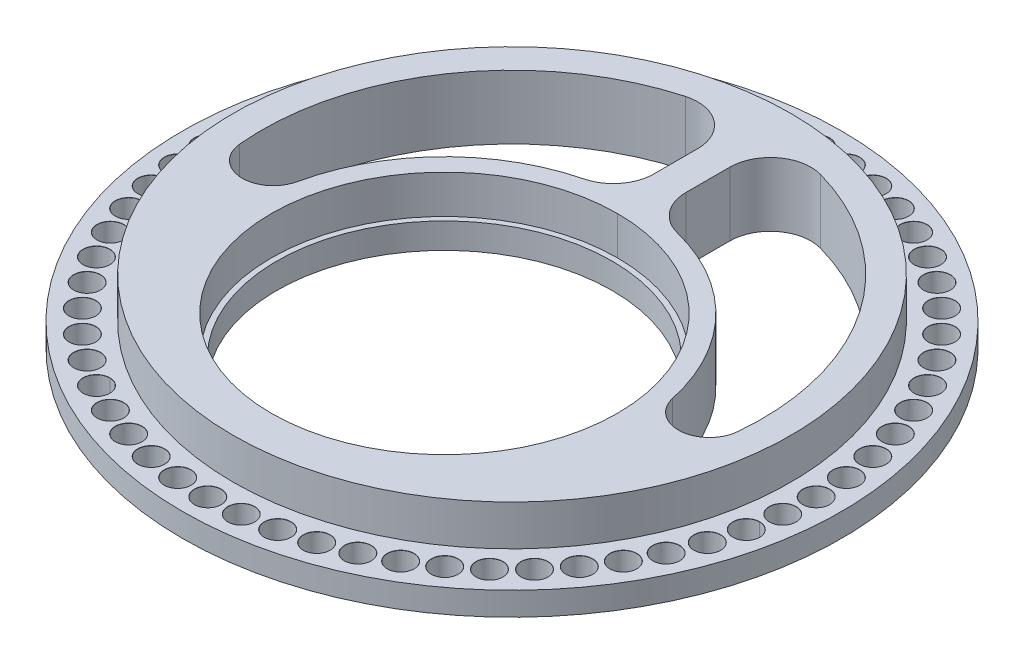
SolidWorks part; units mm, degrees
material "6061-T6 (SS)"
ref_plane "X-Y Datum" through (0, 0, 0) normal (0, 0, 1) x (1, 0, 0)
ref_plane "X-Z Datum" through (0, 0, 0) normal (0, 1, 0) x (1, 0, 0)
ref_plane "Y-Z Datum" through (0, 0, 0) normal (1, 0, 0) x (0, 0, -1)
sketch "Sketch1" plane through (0, 0, 0) normal (0, 1, 0) x (1, 0, 0)
  line L0 (0, 0) -> (0, -12.7) construction
  line L1 (0, -43.0151) -> (0, 43.0151) construction
  line L2 (0, 52.3875) -> (0, 61.9125) construction
  circle A0 centre (0, -12.7) radius 30.988
  circle A1 centre (0, 0) radius 52.3875 construction
  circle A2 centre (0, 0) radius 61.9125
  circle A3 centre (0, 0) radius 57.15 construction
  point P12 (0, 57.15)
  dimension "D2" = 61.976
  dimension "D3" = 104.775
  dimension "D4" = 123.825
  dimension "D5" = 114.3
  dimension "D1" = 12.7
extrude "Slotted-Body Extrude" add sketch "Sketch1" along normal blind 4.191 and the other way blind 0.2032
sketch "Sketch5" plane through (0, 4.191, 0) normal (0, 1, 0) x (1, 0, 0)
  circle A0 centre (0, 0) radius 52.3875 construction
  circle A1 centre (0, 0) radius 52.3875
extrude "Boss-Extrude3" add sketch "Sketch5" along normal blind 7.62
sketch "Sketch6" plane through (0, -0.2032, 0) normal (0, -1, 0) x (1, 0, 0)
  line L0 (0, -79.2756) -> (0, 0) construction
  line L2 (3.014, -37.9067) -> (3.014, -29.6741)
  line L4 (-3.014, -37.9067) -> (-3.014, -29.6741)
  circle A0 centre (0, 12.7) radius 30.988 construction
  circle A1 centre (0, 12.7) radius 30.988 construction
  circle A2 centre (0, 12.7) radius 32.512
  arc A9 (-35.2562, 5.0907) -> (-8.7792, -22.2832) centre (0, 12.7) ccw
  arc A10 (-46.783, 4.406) -> (-12.6921, -45.2435) centre (0, 0) ccw
  arc A11 (-46.783, 4.406) -> (-35.2562, 5.0907) centre (-40.9667, 3.8583) cw
  arc A19 (-3.014, -29.6741) -> (-8.7792, -22.2832) centre (-10.634, -29.6741) ccw
  arc A20 (-3.014, -37.9067) -> (-12.6921, -45.2435) centre (-10.634, -37.9067) cw
  circle A21 centre (0, 0) radius 61.9125 construction
  arc A27 (46.783, 4.406) -> (35.2562, 5.0907) centre (40.9667, 3.8583) ccw
  arc A28 (46.783, 4.406) -> (12.6921, -45.2435) centre (0, 0) cw
  arc A29 (3.014, -37.9067) -> (12.6921, -45.2435) centre (10.634, -37.9067) ccw
  arc A30 (3.014, -29.6741) -> (8.7792, -22.2832) centre (10.634, -29.6741) cw
  arc A31 (35.2562, 5.0907) -> (8.7792, -22.2832) centre (0, 12.7) cw
  point P30 (0, 0)
  point P31 (-3.014, -23.2419)
  point P32 (0, 0)
  point P36 (-3.014, -46.8932)
  dimension "D1" = 65.024
  dimension "D2" = 7.62
  dimension "D3" = 5.842
  dimension "D4" = 46.99
  dimension "D5" = 7.62
  dimension "D6" = 36.068
  dimension "D8" = 8.2326
extrude "Cut-Extrude5" cut sketch "Sketch6" against normal through all
sketch "Sketch8" plane through (0, -0.2032, 0) normal (0, -1, 0) x (1, 0, 0)
  circle A0 centre (0, 12.7) radius 32.512 construction
  circle A1 centre (0, 12.7) radius 32.512
  circle A2 centre (0, 12.7) radius 31.496
  dimension "D1" = 62.992
extrude "Boss-Extrude4" add sketch "Sketch8" against normal blind 4.795 separate body
hole_wizard "Ø5.0mm Dowel Hole2" positions "Sketch9" profile "Sketch10" hole size "Ø5.0" standard "ANSI Metric" end condition through all
sketch "Sketch9" plane through (0, 4.191, 0) normal (0, 1, 0) x (1, 0, 0)
  point P0 (0, 57.15)
sketch "Sketch10" plane through (0, 4.191, -57.15) normal (1, 0, 0) x (0, 0, 1)
  line L0 (0, 0) -> (0, 4.3942)
  line L1 (0, 4.3942) -> (2.5, 4.3942)
  line L2 (2.5, 4.3942) -> (2.5, 0.025)
  line L3 (2.5, 0.025) -> (2.525, 0)
  line L5 (2.525, 0) -> (0, 0)
  line L6 (-2.5, 0.025) -> (-2.525, 0) construction
  line L11 (0, -6.35) -> (0, 107.95) construction
  dimension "Thru Hole Dia." = 5
  dimension "Thru Hole Depth" = 4.3942
  dimension "Near C'Sink Dia." = 5.05
  dimension "Near C'Sink Angle" = 90
pattern_circular "CirPattern1" count 60 over 360 about axis through (0, 0, 0) along (0, 1, 0) of "Ø5.0mm Dowel Hole2"
ref_point "Point1"
ref_plane "Plane1" through (0, 0, 0) normal (1, 0, 0) x (0, 0, -1)
split line "Split Line1"
ref_point "Point2"
ref_point "Point3"
ref_point "Point4"
ref_point "Point5"
split line "Split Line2"
split line "Split Line3"
ref_plane "Plane2" through (-42.4707, 0, 0) normal (-1, 0, 0) x (0, 0, 1)
ref_plane "Plane3" through (55.9011, 0, 0) normal (-1, 0, 0) x (0, 0, 1)
split line "Split Line4"
split line "Split Line5"
sketch "Sketch17" plane through (0, 4.191, 0) normal (0, 1, 0) x (1, 0, 0)
  line L0 (-71.12, 66.6242) -> (71.12, 66.6242) construction
  line L1 (-71.12, -66.6242) -> (71.12, -66.6242) construction
  line L2 (-71.12, -66.6242) -> (-71.12, 66.6242) construction
  line L3 (-71.12, 66.6242) -> (71.12, 66.6242) construction
  line L4 (71.12, -66.6242) -> (71.12, 66.6242) construction
  line L5 (-71.12, -66.6242) -> (71.12, 66.6242) construction
  line L6 (-71.12, 66.6242) -> (-45.1836, 42.3273) construction
  line L7 (-71.12, 88.7603) -> (71.12, 88.7603)
  line L11 (-71.12, 59.8198) -> (-15.9607, 59.8198)
  line L12 (-71.12, 88.7603) -> (71.12, 88.7603)
  line L13 (-71.12, 88.7603) -> (-71.12, -66.6242)
  line L14 (-71.12, -66.6242) -> (71.12, -66.6242)
  line L15 (71.12, 88.7603) -> (71.12, -66.6242)
  line L16 (15.9607, 59.8198) -> (71.12, 59.8198)
  line L17 (0, 0) -> (71.12, -66.6242) construction
  arc A1 (15.9607, 59.8198) -> (-15.9607, 59.8198) centre (0, 0) ccw
  point P0 (0, 0)
  dimension "D1" = 142.24
  dimension "D2" = 133.2484
  dimension "D3" = 22.1361
sketch "Sketch13" plane through (0, 11.811, 0) normal (0, 1, 0) x (1, 0, 0)
  line L0 (3.014, 29.6741) -> (3.014, 37.9067) construction
  line L1 (-3.014, 37.9067) -> (-3.014, 29.6741) construction
  line L2 (3.014, 29.6741) -> (3.014, 37.9067) construction
  line L3 (-3.014, 37.9067) -> (-3.014, 29.6741) construction
  line L4 (-6.062, 37.9067) -> (-6.062, 29.6741)
  line L5 (6.062, 29.6741) -> (6.062, 37.9067)
  circle A0 centre (0, -12.7) radius 31.496 construction
  circle A1 centre (0, -12.7) radius 31.496 construction
  circle A2 centre (0, -12.7) radius 28.448
  arc A3 (35.2562, -5.0907) -> (46.783, -4.406) centre (40.9667, -3.8583) ccw construction
  arc A4 (35.2562, -5.0907) -> (8.7792, 22.2832) centre (0, -12.7) ccw construction
  arc A5 (3.014, 29.6741) -> (8.7792, 22.2832) centre (10.634, 29.6741) ccw construction
  arc A6 (46.783, -4.406) -> (12.6921, 45.2435) centre (0, 0) ccw construction
  arc A7 (12.6921, 45.2435) -> (3.014, 37.9067) centre (10.634, 37.9067) ccw construction
  arc A8 (-46.783, -4.406) -> (-35.2562, -5.0907) centre (-40.9667, -3.8583) ccw construction
  arc A9 (-8.7792, 22.2832) -> (-35.2562, -5.0907) centre (0, -12.7) ccw construction
  arc A10 (-8.7792, 22.2832) -> (-3.014, 29.6741) centre (-10.634, 29.6741) ccw construction
  arc A11 (-3.014, 37.9067) -> (-12.6921, 45.2435) centre (-10.634, 37.9067) ccw construction
  arc A12 (-12.6921, 45.2435) -> (-46.783, -4.406) centre (0, 0) ccw construction
  arc A13 (35.2562, -5.0907) -> (46.783, -4.406) centre (40.9667, -3.8583) ccw construction
  arc A14 (35.2562, -5.0907) -> (8.7792, 22.2832) centre (0, -12.7) ccw construction
  arc A15 (3.014, 29.6741) -> (8.7792, 22.2832) centre (10.634, 29.6741) ccw construction
  arc A16 (46.783, -4.406) -> (12.6921, 45.2435) centre (0, 0) ccw construction
  arc A17 (12.6921, 45.2435) -> (3.014, 37.9067) centre (10.634, 37.9067) ccw construction
  arc A18 (-46.783, -4.406) -> (-35.2562, -5.0907) centre (-40.9667, -3.8583) ccw construction
  arc A19 (-8.7792, 22.2832) -> (-35.2562, -5.0907) centre (0, -12.7) ccw construction
  arc A20 (-8.7792, 22.2832) -> (-3.014, 29.6741) centre (-10.634, 29.6741) ccw construction
  arc A21 (-3.014, 37.9067) -> (-12.6921, 45.2435) centre (-10.634, 37.9067) ccw construction
  arc A22 (-12.6921, 45.2435) -> (-46.783, -4.406) centre (0, 0) ccw construction
  arc A23 (-11.8689, 42.3087) -> (-43.7484, -4.1202) centre (0, 0) ccw
  arc A24 (-43.7484, -4.1202) -> (-38.2356, -4.4477) centre (-40.9667, -3.8583) ccw
  arc A25 (-9.5211, 25.2396) -> (-38.2356, -4.4477) centre (0, -12.7) ccw
  arc A26 (-9.5211, 25.2396) -> (-6.062, 29.6741) centre (-10.634, 29.6741) ccw
  arc A27 (-6.062, 37.9067) -> (-11.8689, 42.3087) centre (-10.634, 37.9067) ccw
  arc A28 (11.8689, 42.3087) -> (6.062, 37.9067) centre (10.634, 37.9067) ccw
  arc A29 (6.062, 29.6741) -> (9.5211, 25.2396) centre (10.634, 29.6741) ccw
  arc A30 (38.2356, -4.4477) -> (9.5211, 25.2396) centre (0, -12.7) ccw
  arc A31 (38.2356, -4.4477) -> (43.7484, -4.1202) centre (40.9667, -3.8583) ccw
  arc A32 (43.7484, -4.1202) -> (11.8689, 42.3087) centre (0, 0) ccw
  dimension "D1" = 3.048
  dimension "D2" = 3.048
sketch "Sketch11" plane through (0, -0.2032, 0) normal (0, -1, 0) x (1, 0, 0)
  line L1 (-61.9125, -61.9125) -> (61.9125, -61.9125)
  line L2 (-61.9125, -61.9125) -> (-61.9125, 61.9125)
  line L3 (-61.9125, 61.9125) -> (61.9125, 61.9125)
  line L4 (61.9125, -61.9125) -> (61.9125, 61.9125)
  line L5 (-61.9125, -61.9125) -> (61.9125, 61.9125) construction
  line L6 (-61.9125, 61.9125) -> (61.9125, -61.9125) construction
  circle A0 centre (0, 0) radius 61.9125 construction
  point P0 (0, 0)
sketch "Sketch14" plane through (0, 4.191, 0) normal (0, 1, 0) x (1, 0, 0)
  line L0 (-61.9125, 61.9125) -> (-61.9125, -61.9125) construction
  line L1 (-61.9125, 61.9125) -> (61.9125, 61.9125) construction
  line L2 (-61.9125, 61.9125) -> (-61.9125, -61.9125) construction
  line L3 (-61.9125, 61.9125) -> (61.9125, 61.9125) construction
  line L7 (-61.9125, -61.9125) -> (61.9125, 61.9125) construction
  line L8 (-61.9125, -61.9125) -> (61.9125, 61.9125)
  line L9 (0, -0.6085) -> (0, 49999.3915) construction
  circle A0 centre (0, 0) radius 61.9125 construction
  circle A2 centre (0, 0) radius 61.9125 construction
  arc A3 (-62.4462, 2.4493) -> (62.4462, 2.4493) centre (0, -0.6085) cw
  arc A4 (-62.4462, 2.4493) -> (-77.6194, 1.8864) centre (-70.0571, 2.822) cw
  arc A5 (0, 61.9125) -> (-3.7531, 76.0115) centre (-4.0041, 68.3957) ccw
  arc A6 (-77.6194, 1.8864) -> (-3.7531, 76.0115) centre (-26.007, 24.3209) cw
  arc A7 (2.4493, -62.4462) -> (1.8864, -77.6194) centre (2.822, -70.0571) ccw
  arc A8 (2.4493, -62.4462) -> (61.9125, 0) centre (-0.6085, 0) ccw
  arc A9 (61.9125, 0) -> (76.0115, -3.7531) centre (68.3957, -4.0041) cw
  arc A10 (1.8864, -77.6194) -> (76.0115, -3.7531) centre (24.3209, -26.007) ccw
  arc A11 (62.4462, 2.4493) -> (77.6194, 1.8864) centre (70.0571, 2.822) ccw
  arc A12 (0, 61.9125) -> (3.7531, 76.0115) centre (4.0041, 68.3957) cw
  arc A13 (77.6194, 1.8864) -> (3.7531, 76.0115) centre (26.007, 24.3209) ccw
  arc A14 (-2.4493, -62.4462) -> (-61.9125, 0) centre (0.6085, 0) cw
  arc A15 (-61.9125, 0) -> (-76.0115, -3.7531) centre (-68.3957, -4.0041) ccw
  arc A16 (-1.8864, -77.6194) -> (-76.0115, -3.7531) centre (-24.3209, -26.007) cw
  arc A17 (-2.4493, -62.4462) -> (-1.8864, -77.6194) centre (-2.822, -70.0571) cw
  point P13 (-61.9125, 0)
  dimension "D1" = 7.62
  dimension "D2" = 7.62
